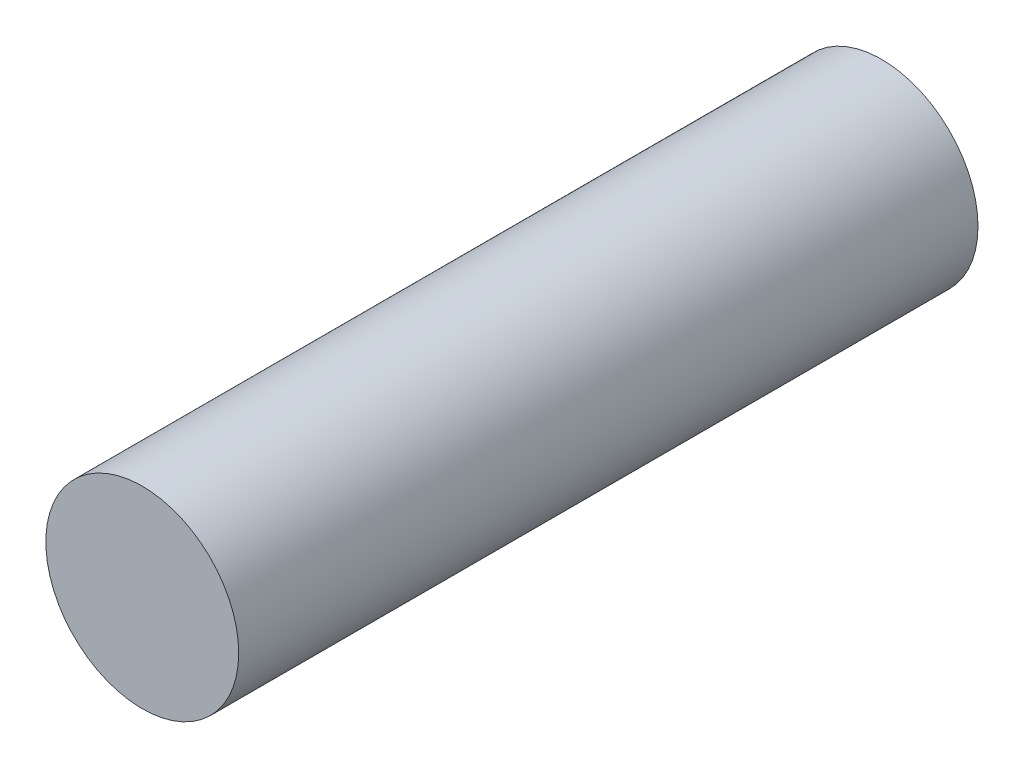
SolidWorks part; units mm, degrees
ref_plane "Plan1" through (0, 0, 0) normal (0, 0, 1) x (1, 0, 0)
ref_plane "Plan2" through (0, 0, 0) normal (0, 1, 0) x (1, 0, 0)
ref_plane "Plan3" through (0, 0, 0) normal (1, 0, 0) x (0, 0, -1)
sketch "Esquisse1" plane through (0, 0, 0) normal (0, 0, 1) x (1, 0, 0)
  circle A0 centre (0, 0) radius 1.5
  dimension "D1" = 3
extrude "Base-Extrusion" add sketch "Esquisse1" along normal blind 11.5
